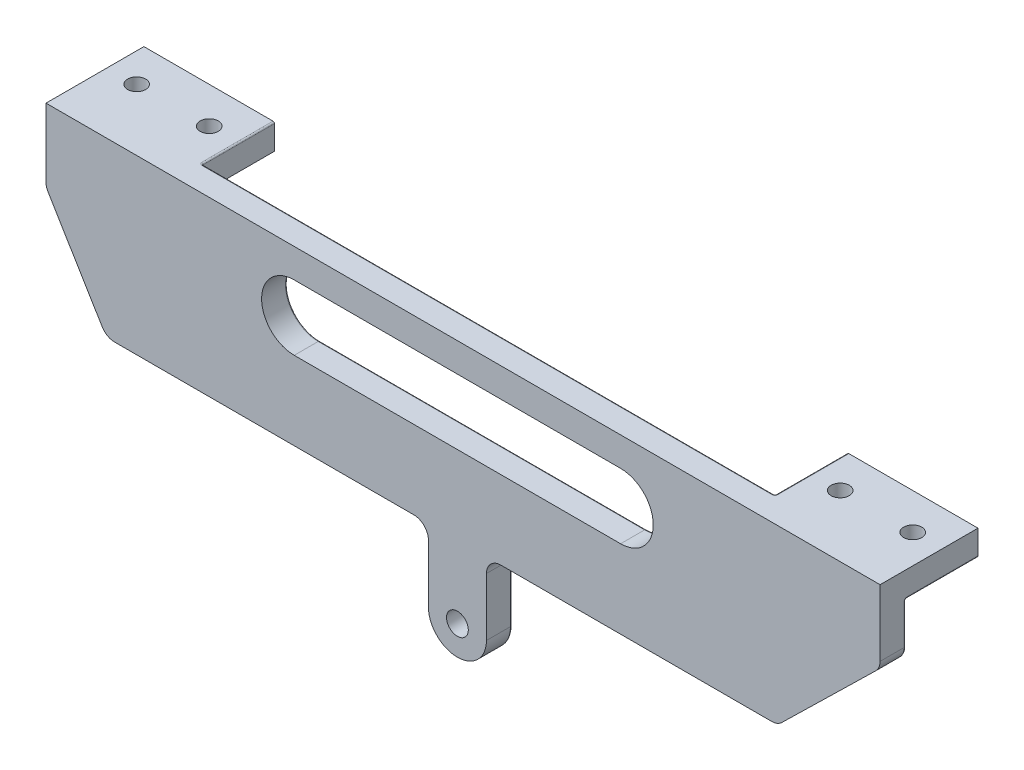
SolidWorks part; units mm, degrees
ref_plane "Front Plane" through (0, 0, 0) normal (0, 0, 1) x (1, 0, 0)
ref_plane "Top Plane" through (0, 0, 0) normal (0, 1, 0) x (1, 0, 0)
ref_plane "Right Plane" through (0, 0, 0) normal (1, 0, 0) x (0, 0, -1)
sketch "Sketch1" plane through (0, 0, 0) normal (0, 0, 1) x (1, 0, 0)
  line L0 (-106.0307, 0) -> (93.9693, 0) construction
  line L1 (-106.0307, 0) -> (-6.0307, 100) construction
  line L2 (-6.0307, 100) -> (93.9693, 0) construction
  line L3 (0, 0) -> (-53.0154, 53.0154) construction
  line L4 (-46.0307, 60) -> (33.9693, 60) construction
  line L5 (-6.0307, 100) -> (-6.0307, 60) construction
  circle A0 centre (-106.0307, 0) radius 20
  circle A1 centre (0, 0) radius 20
  circle A2 centre (93.9693, 0) radius 20
  dimension "D6" = 40
  dimension "D7" = 40
  dimension "D8" = 40
  dimension "D1" = 200
  dimension "D2" = 90
  dimension "D3" = 90
  dimension "D4" = 80
  dimension "D5" = 40
sketch "Sketch2" plane through (0, 0, 0) normal (0, 0, 1) x (1, 0, 0)
  line L0 (-62.5472, 43.4835) -> (-46.0307, 60) construction
  line L2 (-106.0307, 0) -> (-6.0307, 100) construction
  line L3 (-46.0307, 60) -> (33.9693, 60) construction
  line L4 (33.9693, 60) -> (80.5342, 13.435) construction
  line L5 (-6.0307, 100) -> (93.9693, 0) construction
  line L6 (-55.4762, 36.4124) -> (-41.8886, 50)
  line L7 (-41.8886, 50) -> (29.8271, 50)
  line L8 (29.8271, 50) -> (73.4632, 6.364)
  line L9 (-69.6183, 50.5546) -> (-50.1729, 70)
  line L10 (-50.1729, 70) -> (38.1114, 70)
  line L11 (38.1114, 70) -> (87.6053, 20.5061)
  line L12 (-55.4762, 36.4124) -> (-69.6183, 50.5546)
  line L13 (87.6053, 20.5061) -> (73.4632, 6.364)
  line L14 (98.8369, 5.0305) -> (85.2636, 18.1644)
  line L15 (88.8813, -4.8075) -> (76.0143, 8.8101)
  line L16 (85.2636, 18.1644) -> (76.0143, 8.8101)
  line L17 (84.0698, 24.0416) -> (69.9276, 9.8995) construction
  line L18 (-6.0307, 100) -> (-6.0307, 60) construction
  line L19 (-9.5307, 84.85) -> (-12.0307, 70)
  line L20 (-6.0307, 70) -> (-6.0307, 82.2198) construction
  line L21 (-2.5307, 84.85) -> (-0.0307, 70)
  circle A0 centre (93.9693, 0) radius 10 construction
  circle A1 centre (93.9693, 0) radius 3.5
  arc A2 (88.8813, -4.8075) -> (98.8369, 5.0305) centre (93.9693, 0) ccw
  circle A3 centre (93.9693, 0) radius 20 construction
  circle A4 centre (73.4632, 13.435) radius 1
  circle A5 centre (80.5342, 20.5061) radius 1
  circle A6 centre (-6.0307, 60) radius 1.5
  circle A7 centre (-6.0307, 84.85) radius 1.5
  arc A8 (-2.5307, 84.85) -> (-9.5307, 84.85) centre (-6.0307, 84.85) ccw
  circle A9 centre (-53.0154, 53.0154) radius 1.5
  point P45 (-6.0307, 70)
  dimension "D4" = 20
  dimension "D5" = 7
  dimension "D6" = 3
  dimension "D8" = 5
  dimension "D9" = 2
  dimension "D10" = 2
  dimension "D13" = 3
  dimension "D14" = 3
  dimension "D16" = 2
  dimension "D18" = 3
  dimension "D1" = 10
  dimension "D3" = 27.5
  dimension "D7" = 19
  dimension "D11" = 5
  dimension "D12" = 5
  dimension "D15" = 14.85
  dimension "D17" = 6
  dimension "D2" = 10
sketch "Sketch3" plane through (0, 0, 0) normal (0, 0, 1) x (1, 0, 0)
  line L0 (-94.5203, 11.5104) -> (-53.0154, 53.0154) construction
  line L1 (-106.0307, 0) -> (-6.0307, 100) construction
  line L2 (-53.0154, 53.0154) -> (-13.435, 13.435) construction
  line L3 (0, 0) -> (-53.0154, 53.0154) construction
  line L4 (-85.5246, 6.364) -> (-53.0154, 38.8732)
  line L5 (-53.0154, 38.8732) -> (-20.5061, 6.364)
  line L6 (-99.6668, 20.5061) -> (-53.0154, 67.1575)
  line L7 (-53.0154, 67.1575) -> (-6.364, 20.5061)
  line L8 (-95.851, 10.1797) -> (-53.0154, 53.0154) construction
  line L9 (-99.6668, 20.5061) -> (-85.5246, 6.364)
  line L10 (-20.5061, 6.364) -> (-6.364, 20.5061)
  line L11 (-102.9221, 17.2507) -> (-53.0154, 67.1575) construction
  line L12 (-88.78, 3.1086) -> (-53.0154, 38.8732) construction
  line L13 (-110.4492, 4.7673) -> (-96.685, 17.5243)
  line L14 (-106.0307, 0) -> (-96.685, 9.3457) construction
  line L15 (-101.2634, -4.4185) -> (-88.5064, 9.3457)
  line L16 (0, 0) -> (-13.435, 13.435) construction
  line L17 (-4.7673, -4.4185) -> (-17.5243, 9.3457)
  line L18 (4.4185, 4.7673) -> (-9.3457, 17.5243)
  line L19 (-96.1312, 24.0416) -> (-81.9891, 9.8995) construction
  line L20 (-9.8995, 24.0416) -> (-24.0416, 9.8995) construction
  circle A0 centre (-106.0307, 0) radius 10 construction
  circle A1 centre (-106.0307, 0) radius 3.5
  circle A2 centre (0, 0) radius 10 construction
  circle A4 centre (93.9693, 0) radius 10 construction
  circle A6 centre (0, 0) radius 3.5
  circle A7 centre (93.9693, 0) radius 3.5
  circle A8 centre (-106.0307, 0) radius 6.5
  circle A9 centre (0, 0) radius 6.5
  circle A10 centre (93.9693, 0) radius 6.5
  circle A11 centre (-92.5957, 20.5061) radius 1
  circle A12 centre (-85.5246, 13.435) radius 1
  circle A13 centre (-13.435, 20.5061) radius 1
  circle A14 centre (-20.5061, 13.435) radius 1
  circle A16 centre (-53.0154, 53.0154) radius 1.5 construction
  circle A17 centre (-53.0154, 53.0154) radius 1.5
  dimension "D1" = 20
  dimension "D2" = 20
  dimension "D3" = 20
  dimension "D4" = 7
  dimension "D5" = 7
  dimension "D6" = 7
  dimension "D7" = 3
  dimension "D8" = 3
  dimension "D9" = 3
  dimension "D14" = 2
  dimension "D15" = 2
  dimension "D16" = 2
  dimension "D17" = 2
  dimension "D10" = 10
  dimension "D12" = 19
  dimension "D13" = 19
  dimension "D18" = 5
  dimension "D19" = 5
  dimension "D20" = 5
  dimension "D21" = 5
  dimension "D22" = 5
  dimension "D23" = 5
  dimension "D11" = 10
sketch "Sketch4" plane through (0, 0, 0) normal (0, 0, 1) x (1, 0, 0)
  line L0 (-62.7556, 93.8025) -> (52.2444, 93.8025)
  line L1 (52.2444, 93.8025) -> (52.2444, 83.8025)
  line L2 (52.2444, 83.8025) -> (38.1114, 70)
  line L3 (-50.1729, 70) -> (38.1114, 70) construction
  line L4 (38.1114, 70) -> (-54.4235, 70)
  line L5 (-54.4235, 70) -> (-62.7556, 83.8025)
  line L6 (-62.7556, 83.8025) -> (-62.7556, 93.8025)
  line L7 (-2.0307, 60) -> (-2.0307, 70)
  line L8 (-10.0307, 60) -> (-10.0307, 70)
  line L9 (-28.5307, 85.3025) -> (16.4693, 85.3025) construction
  line L10 (-6.0307, 100) -> (-6.0307, 60) construction
  line L12 (-28.5307, 89.8025) -> (16.4693, 89.8025)
  line L13 (-28.5307, 80.8025) -> (16.4693, 80.8025)
  circle A0 centre (-6.0307, 60) radius 1.5 construction
  circle A1 centre (-6.0307, 60) radius 1.5
  arc A2 (-10.0307, 60) -> (-2.0307, 60) centre (-6.0307, 60) ccw
  circle A4 centre (-6.0307, 60) radius 4 construction
  arc A5 (-28.5307, 89.8025) -> (-28.5307, 80.8025) centre (-28.5307, 85.3025) ccw
  arc A6 (16.4693, 80.8025) -> (16.4693, 89.8025) centre (16.4693, 85.3025) ccw
  point P18 (-2.0307, 60)
  point P24 (-6.0307, 85.3025)
  dimension "D1" = 115
  dimension "D2" = 10
  dimension "D4" = 45
  dimension "D5" = 9
  dimension "D6" = 4
  dimension "D3" = 2.5
sketch "Sketch5" plane through (0, 0, 0) normal (0, 0, 1) x (1, 0, 0)
  line L0 (-10.0307, 60) -> (-10.0307, 70) construction
  line L1 (-2.0307, 60) -> (-2.0307, 70) construction
  line L2 (16.4693, 89.8025) -> (-28.5307, 89.8025)
  line L3 (-28.5307, 80.8025) -> (16.4693, 80.8025)
  line L4 (16.4693, 89.8025) -> (-28.5307, 89.8025)
  line L5 (-28.5307, 80.8025) -> (16.4693, 80.8025)
  line L6 (52.2444, 93.8025) -> (-62.7556, 93.8025)
  line L7 (52.2444, 83.8025) -> (52.2444, 93.8025)
  line L8 (38.1114, 70) -> (52.2444, 83.8025)
  line L9 (-54.4235, 70) -> (38.1114, 70)
  line L10 (-62.7556, 83.8025) -> (-54.4235, 70)
  line L11 (-62.7556, 93.8025) -> (-62.7556, 83.8025)
  line L12 (52.2444, 93.8025) -> (-62.7556, 93.8025)
  line L13 (52.2444, 83.8025) -> (52.2444, 93.8025)
  line L14 (38.1114, 70) -> (52.2444, 83.8025)
  line L15 (-54.4235, 70) -> (-10.0307, 70)
  line L16 (-62.7556, 83.8025) -> (-54.4235, 70)
  line L17 (-62.7556, 93.8025) -> (-62.7556, 83.8025)
  line L18 (-10.0307, 60) -> (-10.0307, 70)
  line L19 (-2.0307, 60) -> (-2.0307, 70)
  line L20 (-2.0307, 70) -> (38.1114, 70)
  arc A0 (-10.0307, 60) -> (-2.0307, 60) centre (-6.0307, 60) ccw construction
  circle A1 centre (-6.0307, 60) radius 1.5
  circle A2 centre (-6.0307, 60) radius 1.5
  arc A3 (-10.0307, 60) -> (-2.0307, 60) centre (-6.0307, 60) ccw
  arc A4 (16.4693, 80.8025) -> (16.4693, 89.8025) centre (16.4693, 85.3025) ccw
  arc A5 (-28.5307, 89.8025) -> (-28.5307, 80.8025) centre (-28.5307, 85.3025) ccw
  arc A6 (16.4693, 80.8025) -> (16.4693, 89.8025) centre (16.4693, 85.3025) ccw
  arc A7 (-28.5307, 89.8025) -> (-28.5307, 80.8025) centre (-28.5307, 85.3025) ccw
  dimension "D1" = 0
  dimension "D2" = 0
  dimension "D3" = 0
extrude "Boss-Extrude1" add sketch "Sketch5" along normal blind 3.5
sketch "Sketch6" plane through (0, 93.8025, 0) normal (0, 1, 0) x (1, 0, 0)
  line L0 (-62.7556, 0) -> (-44.7556, 0)
  line L1 (38.1114, 0) -> (-54.4235, 0) construction
  line L2 (-44.7556, 0) -> (-44.7556, 10)
  line L3 (-44.7556, 10) -> (-62.7556, 10)
  line L4 (-62.7556, 10) -> (-62.7556, 0)
  line L5 (-62.7556, 5) -> (-44.7556, 5) construction
  line L6 (-53.7556, 10) -> (-53.7556, 5) construction
  line L7 (-5.2556, -3.5) -> (-5.2556, 26.0659) construction
  line L8 (52.2444, -3.5) -> (-62.7556, -3.5) construction
  line L9 (43.2444, 10) -> (43.2444, 5) construction
  line L10 (52.2444, 5) -> (34.2444, 5) construction
  line L11 (52.2444, 10) -> (52.2444, 0)
  line L12 (34.2444, 10) -> (52.2444, 10)
  line L13 (34.2444, 0) -> (34.2444, 10)
  line L14 (52.2444, 0) -> (34.2444, 0)
  circle A0 centre (-58.7556, 5) radius 1.25
  circle A1 centre (-48.7556, 5) radius 1.25
  circle A2 centre (38.2444, 5) radius 1.25
  circle A3 centre (48.2444, 5) radius 1.25
  dimension "D3" = 2.5
  dimension "D4" = 2.5
  dimension "D1" = 18
  dimension "D2" = 10
  dimension "D5" = 10
extrude "Boss-Extrude2" add sketch "Sketch6" against normal blind 3.5
fillet "Fillet1" radius 2 6 edges at (-10.0307, 70, 1.75) (-2.0307, 70, 1.75) (52.2444, 83.8025, 1.75) (38.1114, 70, 1.75) (-54.4235, 70, 1.75) (-62.7556, 83.8025, 1.75)
fillet "Fillet2" radius 0.2 29 edges at (52.2444, 90.3025, -5) (34.2444, 93.8025, -5) (-44.7556, 93.8025, -5) (-62.7556, 90.3025, -5) (-6.0307, 89.8025, 0) (20.9693, 85.3025, 0) (-6.0307, 80.8025, 0) (-33.0307, 85.3025, 0) (43.2444, 90.3025, 0) (34.2444, 92.0525, 0) (-5.2556, 93.8025, 0) (-44.7556, 92.0525, 0) (-53.7556, 90.3025, 0) (-62.7556, 87.331, 0) (-62.6823, 83.8229, 0) (-58.7374, 77.1461, 0) (-54.2777, 70.2583, 0) (-32.6627, 70, 0) (-10.6165, 69.4142, 0) (-10.0307, 64, 0) (-6.0307, 56, 0) (-2.0307, 64, 0) (-1.4449, 69.4142, 0) (18.633, 70, 0) (38.0512, 70.1477, 0) (45.168, 76.8916, 0) (52.0876, 83.8686, 0) (52.2444, 87.4737, 0) (-4.5307, 60, 0)
